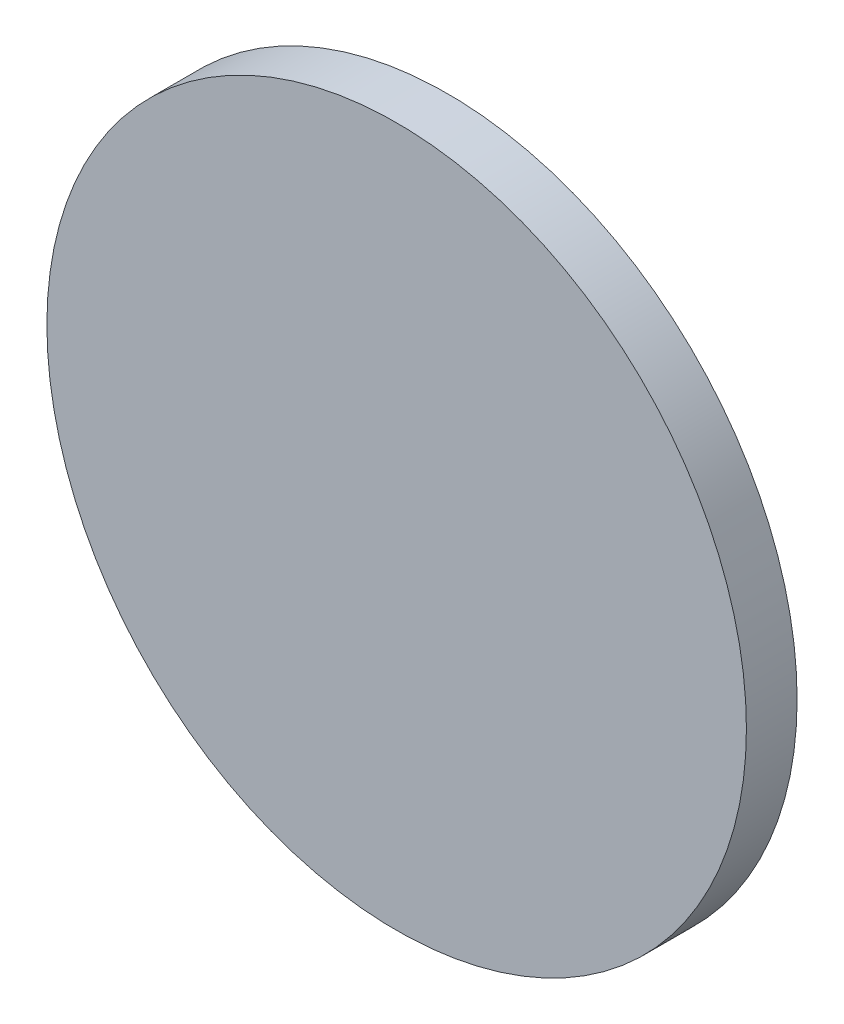
SolidWorks part; units mm, degrees
material "PC High Viscosity"
ref_plane "Front Plane" through (0, 0, 0) normal (0, 0, 1) x (1, 0, 0)
ref_plane "Top Plane" through (0, 0, 0) normal (0, 1, 0) x (1, 0, 0)
ref_plane "Right Plane" through (0, 0, 0) normal (1, 0, 0) x (0, 0, -1)
sketch "Sketch1" plane through (0, 0, 0) normal (0, 0, 1) x (1, 0, 0)
  circle A0 centre (0, 0) radius 21.9075
  dimension "D1" = 43.815
extrude "Boss-Extrude1" add sketch "Sketch1" along normal blind 3.175
